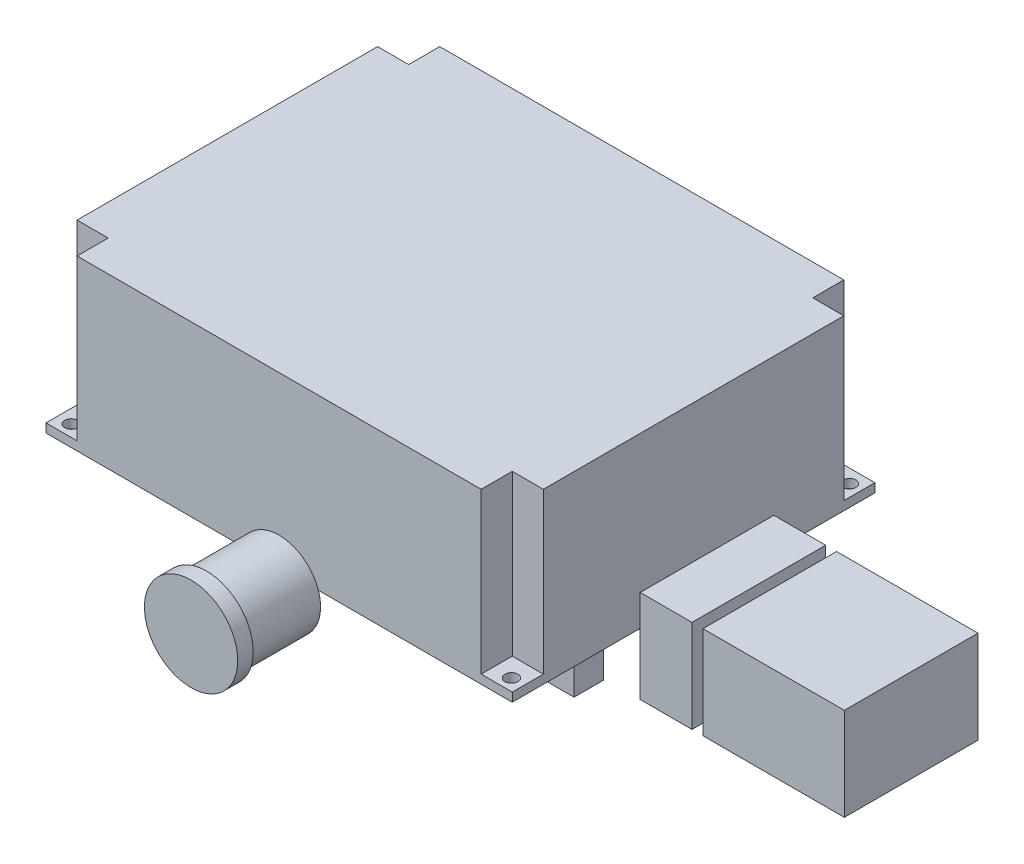
SolidWorks part; units mm, degrees
ref_plane "Front Plane" through (0, 0, 0) normal (0, 0, 1) x (1, 0, 0)
ref_plane "Top Plane" through (0, 0, 0) normal (0, 1, 0) x (1, 0, 0)
ref_plane "Right Plane" through (0, 0, 0) normal (1, 0, 0) x (0, 0, -1)
sketch "Sketch2" plane through (0, 0, 0) normal (0, 1, 0) x (1, 0, 0)
  line L1 (0, 0) -> (90, 0)
  line L2 (0, 0) -> (0, 70)
  line L3 (0, 70) -> (90, 70)
  line L4 (90, 0) -> (90, 70)
  dimension "D1" = 90
  dimension "D2" = 70
extrude "Boss-Extrude1" add sketch "Sketch2" along normal blind 32.6
sketch "Sketch4" plane through (0, 0, 0) normal (0, 0, 1) x (1, 0, 0)
  line L0 (0, 0) -> (90, 0) construction
  line L1 (90, 32.6) -> (90, 0) construction
  circle A0 centre (45, -2.57) radius 8
  dimension "D1" = 2.57
  dimension "D2" = 16
  dimension "D3" = 45
extrude "Boss-Extrude2" add sketch "Sketch4" along normal blind 14
sketch "Sketch6" plane through (0, 0, 0) normal (0, -1, 0) x (-1, 0, 0)
  line L0 (-90, 0) -> (-90, 70) construction
  line L1 (-78.52, 52.7) -> (-85.12, 52.7)
  line L2 (-78.52, 52.7) -> (-78.52, 58.4)
  line L3 (-78.52, 58.4) -> (-85.12, 58.4)
  line L4 (-85.12, 52.7) -> (-85.12, 58.4)
  line L5 (-90, 70) -> (0, 70) construction
  point P4 (-81.82, 52.7)
  point P5 (-85.12, 55.55)
  dimension "D1" = 5.7
  dimension "D2" = 6.6
  dimension "D3" = 4.88
  dimension "D4" = 11.6
sketch "Sketch7" plane through (0, 0, 0) normal (0, -1, 0) x (1, 0, 0)
  line L1 (85.12, -22.5) -> (78.52, -22.5)
  line L2 (85.12, -22.5) -> (85.12, -16.8)
  line L3 (85.12, -16.8) -> (78.52, -16.8)
  line L4 (78.52, -22.5) -> (78.52, -16.8)
  line L6 (0, 0) -> (37.424, 0) construction
  line L7 (90, 0) -> (90, -70) construction
  point P4 (81.82, -22.5)
  point P5 (78.52, -19.65)
  dimension "D1" = 5.7
  dimension "D2" = 6.6
  dimension "D3" = 16.8
  dimension "D4" = 4.88
sketch "Sketch10" plane through (0, 0, 0) normal (0, -1, 0) x (1, 0, 0)
  line L1 (85.12, -40.1) -> (78.52, -40.1)
  line L2 (85.12, -40.1) -> (85.12, -34.4)
  line L3 (85.12, -34.4) -> (78.52, -34.4)
  line L4 (78.52, -40.1) -> (78.52, -34.4)
  line L6 (78.52, -52.7) -> (85.12, -52.7) construction
  line L7 (90, 0) -> (90, -70) construction
  point P4 (81.82, -40.1)
  point P5 (78.52, -37.25)
  dimension "D1" = 5.7
  dimension "D2" = 6.6
  dimension "D3" = 12.6
  dimension "D4" = 4.88
extrude "Boss-Extrude3" add sketch "Sketch6" along normal blind 10
extrude "Boss-Extrude4" add sketch "Sketch10" along normal blind 10
extrude "Boss-Extrude5" add sketch "Sketch7" along normal blind 10
sketch "Sketch11" plane through (0, 32.6, 0) normal (0, 1, 0) x (1, 0, 0)
  line L0 (90, 0) -> (90, 70) construction
  line L1 (0, 0) -> (90, 0) construction
  circle A0 centre (87.55, 2.29) radius 1.25
  dimension "D1" = 2.45
  dimension "D3" = 2.5
  dimension "D2" = 2.29
sketch "Sketch12" plane through (0, 32.6, 0) normal (0, 1, 0) x (1, 0, 0)
  line L2 (90, 0) -> (90, 70) construction
  line L4 (90, 70) -> (0, 70) construction
  circle A0 centre (87.71, 67.37) radius 1.25
  dimension "D1" = 2.29
  dimension "D3" = 2.5
  dimension "D2" = 2.63
sketch "Sketch14" plane through (0, 32.6, 0) normal (0, 1, 0) x (1, 0, 0)
  line L2 (0, 0) -> (90, 0) construction
  line L3 (0, 70) -> (0, 0) construction
  circle A0 centre (2.63, 2.25) radius 1.25
  dimension "D1" = 2.25
  dimension "D3" = 2.5
  dimension "D2" = 2.63
sketch "Sketch15" plane through (0, 32.6, 0) normal (0, 1, 0) x (1, 0, 0)
  line L0 (90, 70) -> (0, 70) construction
  line L2 (0, 70) -> (0, 0) construction
  circle A0 centre (2.61, 67.35) radius 1.25
  dimension "D1" = 2.61
  dimension "D3" = 2.5
  dimension "D2" = 2.65
extrude "Cut-Extrude1" cut sketch "Sketch11" against normal through all both and the other way through all
extrude "Cut-Extrude2" cut sketch "Sketch15" against normal through all both and the other way through all
extrude "Cut-Extrude3" cut sketch "Sketch14" against normal through all both and the other way through all
extrude "Cut-Extrude4" cut sketch "Sketch12" against normal through all both and the other way through all
sketch "Sketch16" plane through (0, 32.6, 0) normal (0, 1, 0) x (1, 0, 0)
  line L1 (0, 70) -> (6, 70)
  line L2 (0, 70) -> (0, 64)
  line L3 (0, 64) -> (6, 64)
  line L4 (6, 70) -> (6, 64)
  dimension "D1" = 6
  dimension "D2" = 6
sketch "Sketch17" plane through (0, 32.6, 0) normal (0, 1, 0) x (1, 0, 0)
  line L0 (90, 0) -> (90, 70) construction
  line L1 (84, 70) -> (90, 70)
  line L2 (84, 70) -> (84, 64)
  line L3 (84, 64) -> (90, 64)
  line L4 (90, 70) -> (90, 64)
  line L5 (90, 70) -> (0, 70) construction
  dimension "D1" = 6
  dimension "D2" = 6
  dimension "D3" = 0
  dimension "D4" = 0
sketch "Sketch18" plane through (0, 32.6, 0) normal (0, 1, 0) x (1, 0, 0)
  line L0 (0, 0) -> (90, 0) construction
  line L1 (84, 6) -> (90, 6)
  line L2 (84, 6) -> (84, 0)
  line L3 (84, 0) -> (90, 0)
  line L4 (90, 6) -> (90, 0)
  line L5 (90, 0) -> (90, 70) construction
  dimension "D1" = 6
  dimension "D2" = 6
  dimension "D3" = 0
  dimension "D4" = 0
sketch "Sketch19" plane through (0, 32.6, 0) normal (0, 1, 0) x (1, 0, 0)
  line L1 (0, 6) -> (6, 6)
  line L2 (0, 6) -> (0, 0)
  line L3 (0, 0) -> (6, 0)
  line L4 (6, 6) -> (6, 0)
  line L6 (0, 70) -> (0, 0) construction
  line L7 (0, 0) -> (90, 0) construction
  dimension "D1" = 6
  dimension "D2" = 6
  dimension "D3" = 0
  dimension "D4" = 0
extrude "Cut-Extrude5" cut sketch "Sketch16" against normal offset from surface (30.9 mm away) 1.7 up to face at (87.71, 0, -68.62)
extrude "Cut-Extrude6" cut sketch "Sketch19" against normal offset from surface (30.9 mm away) 1.7 up to face at (87.71, 0, -68.62)
extrude "Cut-Extrude7" cut sketch "Sketch18" against normal offset from surface (30.9 mm away) 1.7 up to face at (87.71, 0, -68.62)
extrude "Cut-Extrude8" cut sketch "Sketch17" against normal offset from surface (30.9 mm away) 1.7 up to face at (87.71, 0, -68.62)
sketch "Sketch20" plane through (90, 0, 0) normal (1, 0, 0) x (0, 0, -1)
  line L1 (24.7, 6) -> (50.5, 6)
  line L2 (24.7, 6) -> (24.7, -11.9)
  line L3 (24.7, -11.9) -> (50.5, -11.9)
  line L4 (50.5, 6) -> (50.5, -11.9)
  line L5 (52.7, -10) -> (52.7, 0) construction
  line L6 (0, 0) -> (70, 0) construction
  dimension "D1" = 25.8
  dimension "D2" = 17.9
  dimension "D3" = 2.2
  dimension "D4" = 6
extrude "Boss-Extrude6" add sketch "Sketch20" along normal blind 39.4 contours L3 L4 L1 L2
sketch "Sketch22" plane through (0, 0, -50.5) normal (0, 0, -1) x (-1, 0, 0)
  line L0 (-129.4, 6) -> (-90, 6) construction
  line L1 (-102.1, 6) -> (-100, 6)
  line L2 (-102.1, 6) -> (-102.1, -11.9)
  line L3 (-102.1, -11.9) -> (-100, -11.9)
  line L4 (-100, 6) -> (-100, -11.9)
  line L5 (-129.4, -11.9) -> (-90, -11.9) construction
  line L6 (-90, 6) -> (-90, 0) construction
  dimension "D1" = 0
  dimension "D2" = 0
  dimension "D3" = 10
  dimension "D4" = 2.1
extrude "Cut-Extrude9" cut sketch "Sketch22" against normal blind 2.75
sketch "Sketch24" plane through (0, 6, 0) normal (0, 1, 0) x (1, 0, 0)
  line L0 (129.4, 24.7) -> (90, 24.7) construction
  line L1 (100, 50.5) -> (102.1, 50.5)
  line L2 (100, 50.5) -> (100, 24.7)
  line L3 (100, 24.7) -> (102.1, 24.7)
  line L4 (102.1, 50.5) -> (102.1, 24.7)
  dimension "D1" = 2.1
extrude "Cut-Extrude10" cut sketch "Sketch24" against normal blind 2.75
sketch "Sketch25" plane through (0, 0, -24.7) normal (0, 0, 1) x (1, 0, 0)
  line L0 (129.4, -11.9) -> (90, -11.9) construction
  line L1 (100, 6) -> (102.1, 6)
  line L2 (100, 6) -> (100, -11.9)
  line L3 (100, -11.9) -> (102.1, -11.9)
  line L4 (102.1, 6) -> (102.1, -11.9)
  dimension "D1" = 0
  dimension "D2" = 2.1
extrude "Cut-Extrude11" cut sketch "Sketch25" against normal blind 2.75
sketch "Sketch26" plane through (0, -11.9, 0) normal (0, -1, 0) x (-1, 0, 0)
  line L0 (-129.4, 50.5) -> (-102.1, 50.5) construction
  line L1 (-100, 24.7) -> (-102.1, 24.7)
  line L2 (-100, 24.7) -> (-100, 50.5)
  line L3 (-100, 50.5) -> (-102.1, 50.5)
  line L4 (-102.1, 24.7) -> (-102.1, 50.5)
  dimension "D1" = 0
  dimension "D2" = 2.1
extrude "Cut-Extrude12" cut sketch "Sketch26" against normal blind 2.75
sketch "Sketch27" plane through (0, 0, 14) normal (0, 0, 1) x (1, 0, 0)
  circle A0 centre (45, -2.57) radius 9
  dimension "D1" = 18
extrude "Boss-Extrude7" add sketch "Sketch27" along normal blind 3 contours A0
